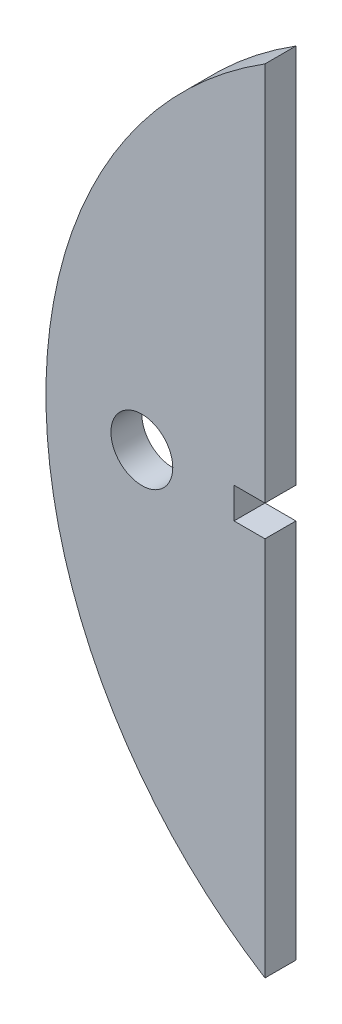
SolidWorks part; units mm, degrees
material "Cedar"
ref_plane "Front Plane" through (0, 0, 0) normal (0, 0, 1) x (1, 0, 0)
ref_plane "Top Plane" through (0, 0, 0) normal (0, 1, 0) x (1, 0, 0)
ref_plane "Right Plane" through (0, 0, 0) normal (1, 0, 0) x (0, 0, -1)
sketch "Sketch1" plane through (0, 0, 0) normal (0, 0, 1) x (1, 0, 0)
  line L0 (0, 0) -> (-47.9425, 0) construction
  line L1 (-28.6385, 1.5875) -> (-25.4635, 1.5875)
  line L2 (-28.6385, 1.5875) -> (-28.6385, -1.5875)
  line L3 (-28.6385, -1.5875) -> (-25.4635, -1.5875)
  line L4 (-25.4635, 1.5875) -> (-25.4635, -1.5875) construction
  line L5 (-25.4635, 1.5875) -> (-25.4635, 40.6213)
  line L6 (-25.4635, -1.5875) -> (-25.4635, -40.6213)
  arc A0 (-25.4635, 40.6213) -> (-25.4635, -40.6213) centre (0, 0) ccw
  circle A1 centre (-38.1, 0) radius 3.175
  dimension "D1" = 95.885
  dimension "D2" = 6.35
  dimension "D3" = 38.1
  dimension "D4" = 3.175
  dimension "D5" = 3.175
  dimension "D6" = 28.6385
extrude "Boss-Extrude1" add sketch "Sketch1" along normal blind 3.175
